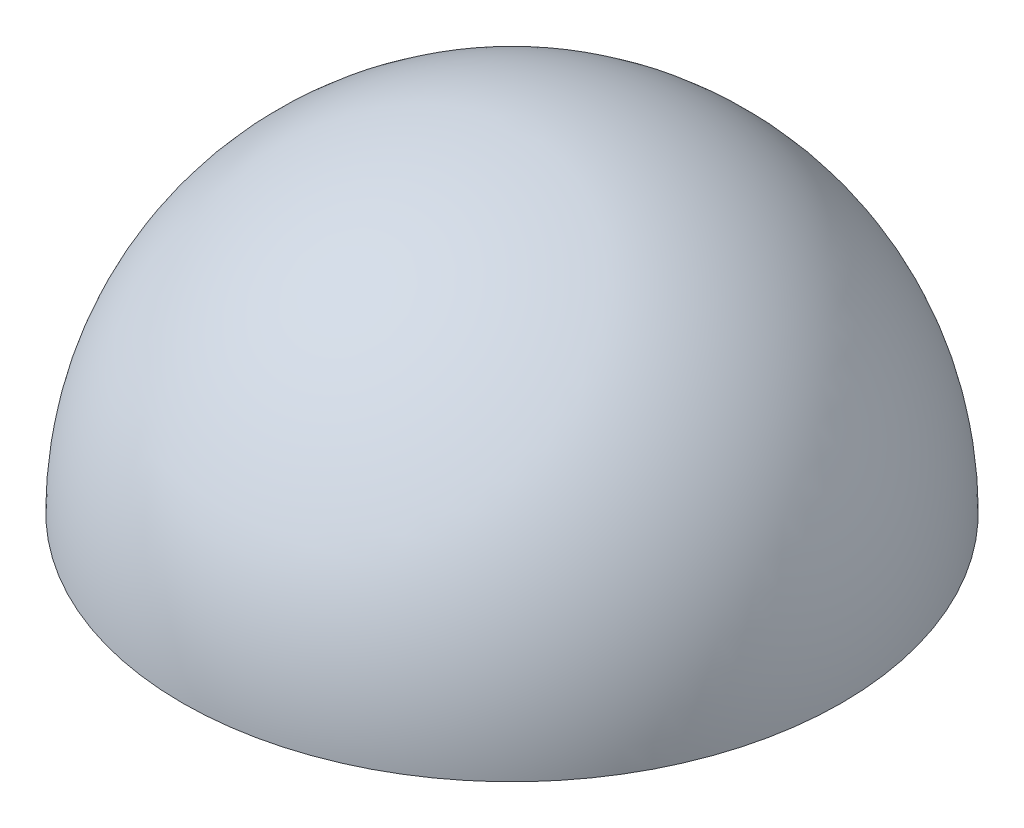
SolidWorks part; units mm, degrees
ref_plane "Front Plane" through (0, 0, 0) normal (0, 0, 1) x (1, 0, 0)
ref_plane "Top Plane" through (0, 0, 0) normal (0, 1, 0) x (1, 0, 0)
ref_plane "Right Plane" through (0, 0, 0) normal (1, 0, 0) x (0, 0, -1)
sketch "Sketch1" plane through (0, 0, 0) normal (0, 0, 1) x (1, 0, 0)
  line L0 (0, 0) -> (0, 160) construction
  line L1 (0, 0) -> (160, 0) construction
  line L2 (0, 0) -> (160, 0)
  line L3 (0, 0) -> (0, 160)
  circle A0 centre (0, 0) radius 160
  dimension "D1" = 160
  dimension "D2" = 160
revolve "Revolve1" add sketch "Sketch1" angle 360 about L0
sketch "Sketch6" plane through (0, 0, 0) normal (0, -1, 0) x (1, 0, 0)
  circle A0 centre (0, 0) radius 5
